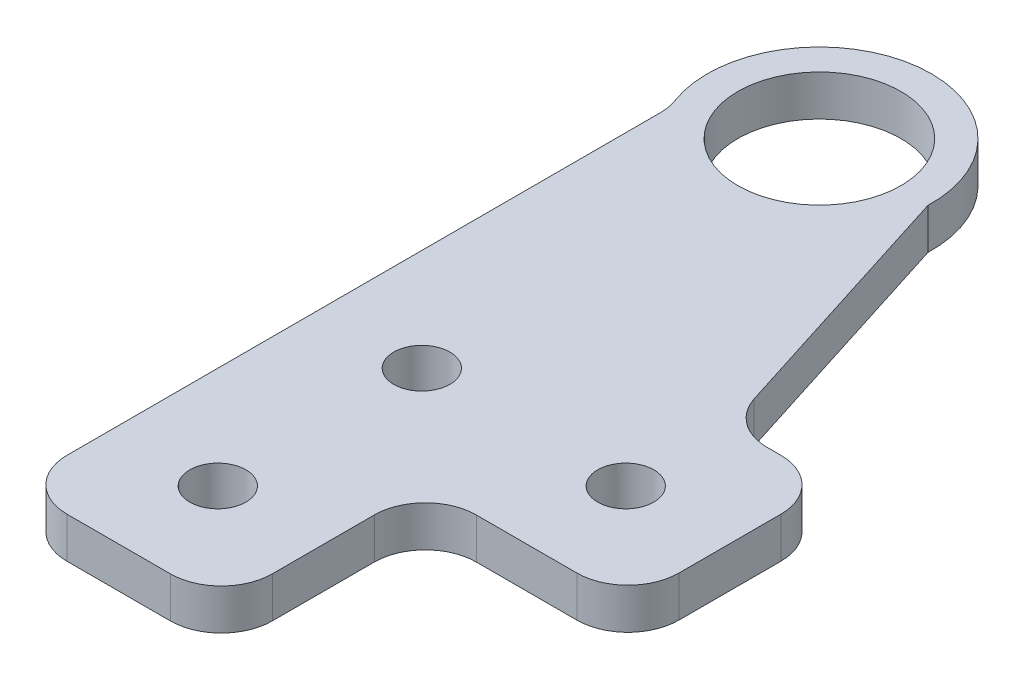
SolidWorks part; units mm, degrees
ref_plane "Alzado" through (0, 0, 0) normal (0, 0, 1) x (1, 0, 0)
ref_plane "Planta" through (0, 0, 0) normal (0, 1, 0) x (1, 0, 0)
ref_plane "Vista lateral" through (0, 0, 0) normal (1, 0, 0) x (0, 0, -1)
sketch "Croquis1" plane through (0, 0, 0) normal (0, 1, 0) x (1, 0, 0)
  line L0 (-19.6831, 22.9418) -> (-19.6831, -35.2493)
  line L1 (-14.6831, -40.2493) -> (-4.5496, -40.2493)
  line L2 (0.4504, -35.2493) -> (0.4504, -25.2493)
  line L3 (5.4504, -20.2493) -> (15.3169, -20.2493)
  line L4 (20.3169, -15.2493) -> (20.3169, -5.2493)
  line L5 (13.9772, -0.2493) -> (15.3169, -0.2493)
  line L6 (9.2109, 3.2398) -> (1.3026, 28.1884)
  circle A0 centre (10.3169, -10.4609) radius 2.75
  circle A1 centre (-9.6831, -10.4609) radius 2.75
  circle A2 centre (-9.6831, -30.4609) radius 2.75
  arc A3 (1.3026, 28.1884) -> (-19.9984, 24.6892) centre (-9.692, 28.5336) ccw
  arc A4 (-19.9984, 24.6892) -> (-19.6831, 22.9418) centre (-24.6831, 22.9418) cw
  arc A5 (9.2109, 3.2398) -> (13.9772, -0.2493) centre (13.9772, 4.7507) ccw
  arc A6 (20.3169, -5.2493) -> (15.3169, -0.2493) centre (15.3169, -5.2493) ccw
  arc A7 (20.3169, -15.2493) -> (15.3169, -20.2493) centre (15.3169, -15.2493) cw
  arc A8 (5.4504, -20.2493) -> (0.4504, -25.2493) centre (5.4504, -25.2493) ccw
  arc A9 (0.4504, -35.2493) -> (-4.5496, -40.2493) centre (-4.5496, -35.2493) cw
  arc A10 (-19.6831, -35.2493) -> (-14.6831, -40.2493) centre (-14.6831, -35.2493) ccw
  circle A11 centre (-9.692, 28.5336) radius 8
  point P17 (-19.6831, 23.9316)
  point P22 (20.3169, -0.2493)
  point P25 (20.3169, -20.2493)
  point P28 (0.4504, -20.2493)
  point P31 (0.4504, -40.2493)
  point P34 (-19.6831, -40.2493)
  dimension "D1" = 5.5
  dimension "D6" = 5
  dimension "D7" = 5.5
  dimension "D8" = 5.5
  dimension "D10" = 16
  dimension "D2" = 20.1335
  dimension "D3" = 64.1809
  dimension "D4" = 20
  dimension "D5" = 20
  dimension "D9" = 20
extrude "Saliente-Extruir1" add sketch "Croquis1" along normal blind 4
